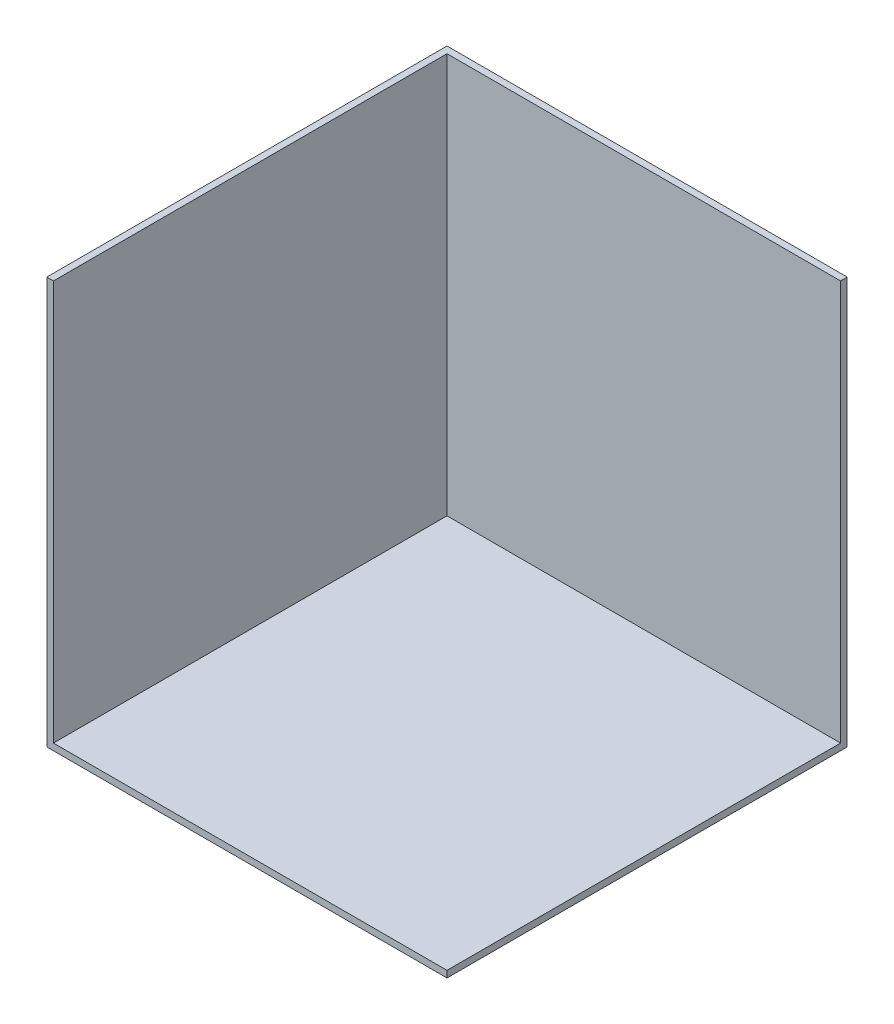
SolidWorks part; units mm, degrees
ref_plane "Front Plane" through (0, 0, 0) normal (0, 0, 1) x (1, 0, 0)
ref_plane "Top Plane" through (0, 0, 0) normal (0, 1, 0) x (1, 0, 0)
ref_plane "Right Plane" through (0, 0, 0) normal (1, 0, 0) x (0, 0, -1)
sketch "Sketch1" plane through (0, 0, 0) normal (0, 1, 0) x (1, 0, 0)
  line L1 (-3000, 3000) -> (3000, 3000)
  line L2 (-3000, 3000) -> (-3000, -3000)
  line L3 (-3000, -3000) -> (3000, -3000)
  line L4 (3000, 3000) -> (3000, -3000)
  line L5 (-3000, 3000) -> (3000, -3000) construction
  line L6 (-3000, -3000) -> (3000, 3000) construction
  point P0 (0, 0)
  dimension "D1" = 6000
  dimension "D2" = 6000
extrude "Boss-Extrude2" add sketch "Sketch1" along normal blind 100
sketch "Sketch2" plane through (0, 100, 0) normal (0, 1, 0) x (1, 0, 0)
  line L0 (3000, 2900) -> (-2900, 2900)
  line L1 (-2900, 2900) -> (-2900, -3000)
  line L4 (3000, -3000) -> (3000, 3000)
  line L5 (3000, 3000) -> (-3000, 3000)
  line L6 (-3000, 3000) -> (-3000, -3000)
  line L7 (-3000, -3000) -> (3000, -3000)
  line L8 (3000, 2900) -> (3000, 3000)
  line L9 (3000, 3000) -> (-3000, 3000)
  line L10 (-3000, 3000) -> (-3000, -3000)
  line L11 (-3000, -3000) -> (-2900, -3000)
  dimension "D2" = 100
  dimension "D3" = 100
  dimension "D1" = 0
extrude "Boss-Extrude3" add sketch "Sketch2" along normal blind 6000
